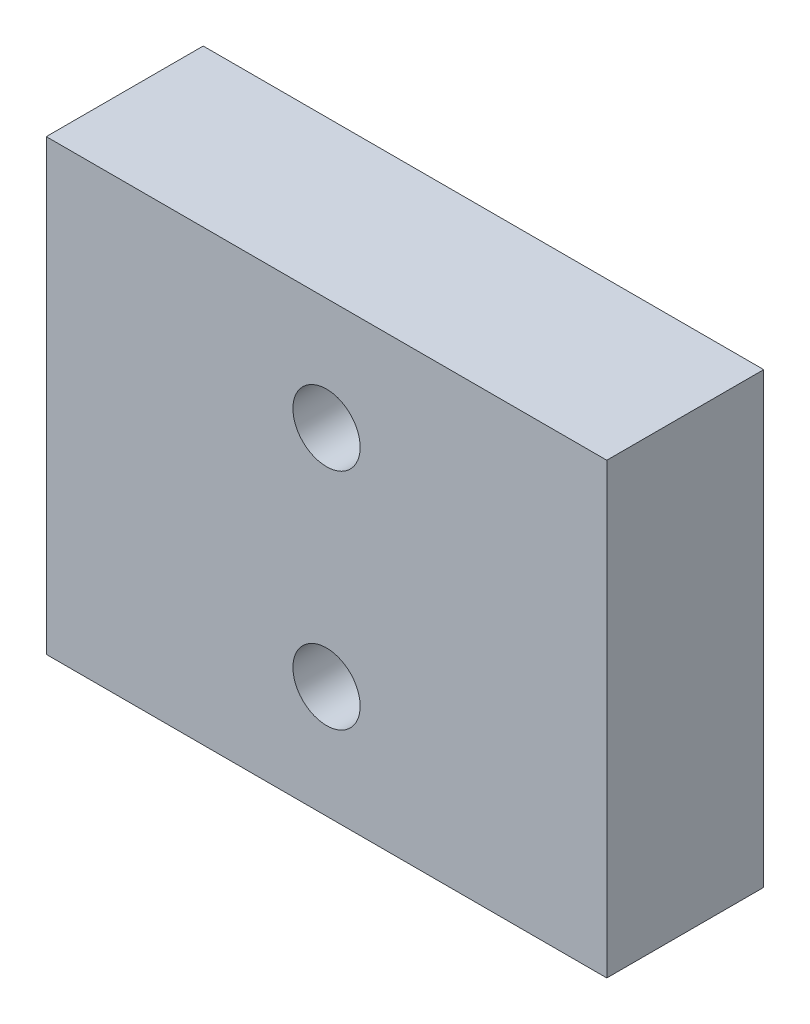
SolidWorks part; units mm, degrees
ref_plane "Plan de face" through (0, 0, 0) normal (0, 0, 1) x (1, 0, 0)
ref_plane "Plan de dessus" through (0, 0, 0) normal (0, 1, 0) x (1, 0, 0)
ref_plane "Plan de droite" through (0, 0, 0) normal (1, 0, 0) x (0, 0, -1)
sketch "Esquisse1" plane through (0, 0, 0) normal (0, 0, 1) x (1, 0, 0)
  line L1 (0, 0) -> (25, 0)
  line L2 (0, 0) -> (0, 20)
  line L3 (0, 20) -> (25, 20)
  line L4 (25, 0) -> (25, 20)
  dimension "D1" = 25
  dimension "D2" = 20
extrude "Boss.-Extru.1" add sketch "Esquisse1" along normal blind 7
sketch "Esquisse2" plane through (0, 0, 7) normal (0, 0, 1) x (1, 0, 0)
  line L2 (0, 20) -> (0, 0) construction
  line L3 (25, 20) -> (0, 20) construction
  circle A0 centre (12.5, 15) radius 1.5
  circle A1 centre (12.5, 5) radius 1.5
  dimension "D1" = 3
  dimension "D2" = 3
  dimension "D3" = 10
  dimension "D4" = 12.5
  dimension "D5" = 12.5
  dimension "D6" = 5
extrude "Enlèv. mat.-Extru.1" cut sketch "Esquisse2" against normal blind 3
